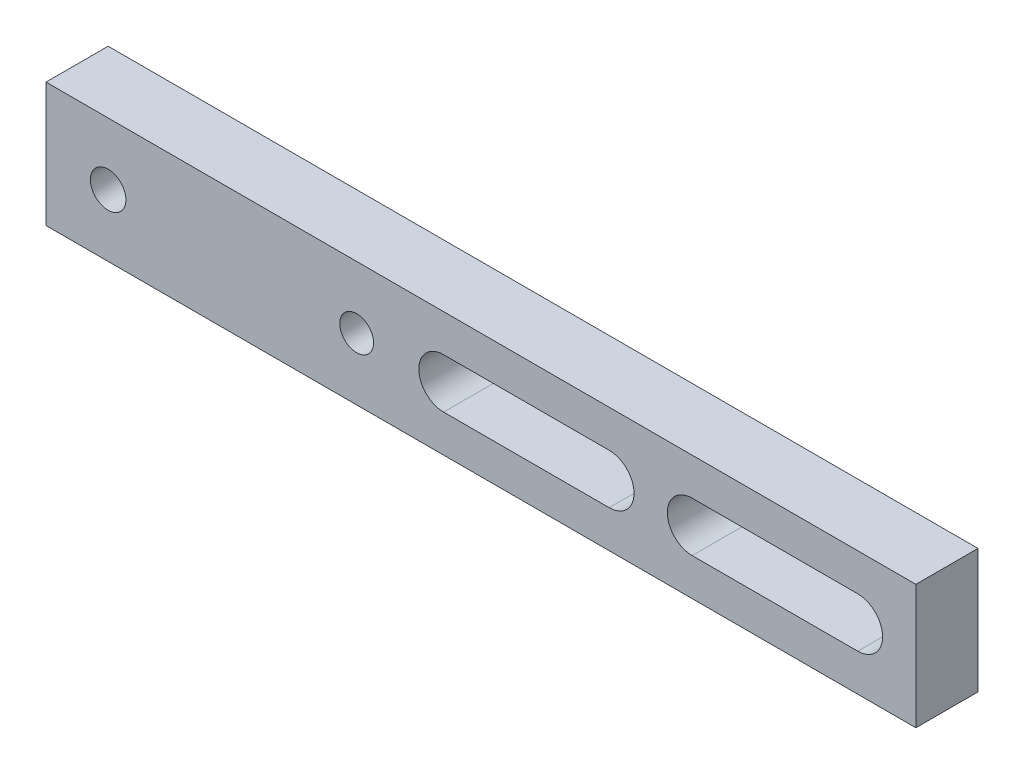
SolidWorks part; units mm, degrees
ref_plane "Front Plane" through (0, 0, 0) normal (0, 0, 1) x (1, 0, 0)
ref_plane "Top Plane" through (0, 0, 0) normal (0, 1, 0) x (1, 0, 0)
ref_plane "Right Plane" through (0, 0, 0) normal (1, 0, 0) x (0, 0, -1)
sketch "Sketch1" plane through (0, 0, 0) normal (0, 0, 1) x (1, 0, 0)
  line L1 (-10.2152, 18.6359) -> (78.6848, 18.6359)
  line L2 (-10.2152, 18.6359) -> (-10.2152, 5.9359)
  line L3 (-10.2152, 5.9359) -> (78.6848, 5.9359)
  line L4 (78.6848, 18.6359) -> (78.6848, 5.9359)
  dimension "D1" = 88.9
  dimension "D2" = 12.7
extrude "Boss-Extrude1" add sketch "Sketch1" along normal blind 6.35
sketch "Sketch3" plane through (0, 0, 6.35) normal (0, 0, 1) x (1, 0, 0)
  line L0 (55.8248, 12.2859) -> (72.7412, 12.2859) construction
  line L1 (55.8248, 14.8259) -> (72.7412, 14.8259)
  line L2 (55.8248, 9.7459) -> (72.7412, 9.7459)
  line L3 (47.3412, 12.2859) -> (30.4248, 12.2859) construction
  line L4 (47.3412, 9.7459) -> (30.4248, 9.7459)
  line L5 (47.3412, 14.8259) -> (30.4248, 14.8259)
  line L6 (-10.2152, 5.9359) -> (78.6848, 5.9359) construction
  line L7 (-10.2152, 18.6359) -> (-10.2152, 5.9359) construction
  arc A0 (55.8248, 14.8259) -> (55.8248, 9.7459) centre (55.8248, 12.2859) ccw
  arc A1 (72.7412, 9.7459) -> (72.7412, 14.8259) centre (72.7412, 12.2859) ccw
  arc A2 (47.3412, 9.7459) -> (47.3412, 14.8259) centre (47.3412, 12.2859) ccw
  arc A3 (30.4248, 14.8259) -> (30.4248, 9.7459) centre (30.4248, 12.2859) ccw
  circle A4 centre (21.5348, 12.2859) radius 1.7295
  circle A5 centre (-3.8652, 12.2859) radius 1.8162
  point P2 (64.283, 12.2859)
  point P9 (38.883, 12.2859)
  dimension "D1" = 2.54
  dimension "D3" = 2.54
  dimension "D2" = 16.9164
  dimension "D4" = 16.9164
  dimension "D5" = 6.35
  dimension "D6" = 6.35
  dimension "D7" = 6.35
  dimension "D8" = 25.4
  dimension "D9" = 40.64
  dimension "D10" = 25.4
  dimension "D11" = 6.35
extrude "Cut-Extrude1" cut sketch "Sketch3" against normal blind 6.35
